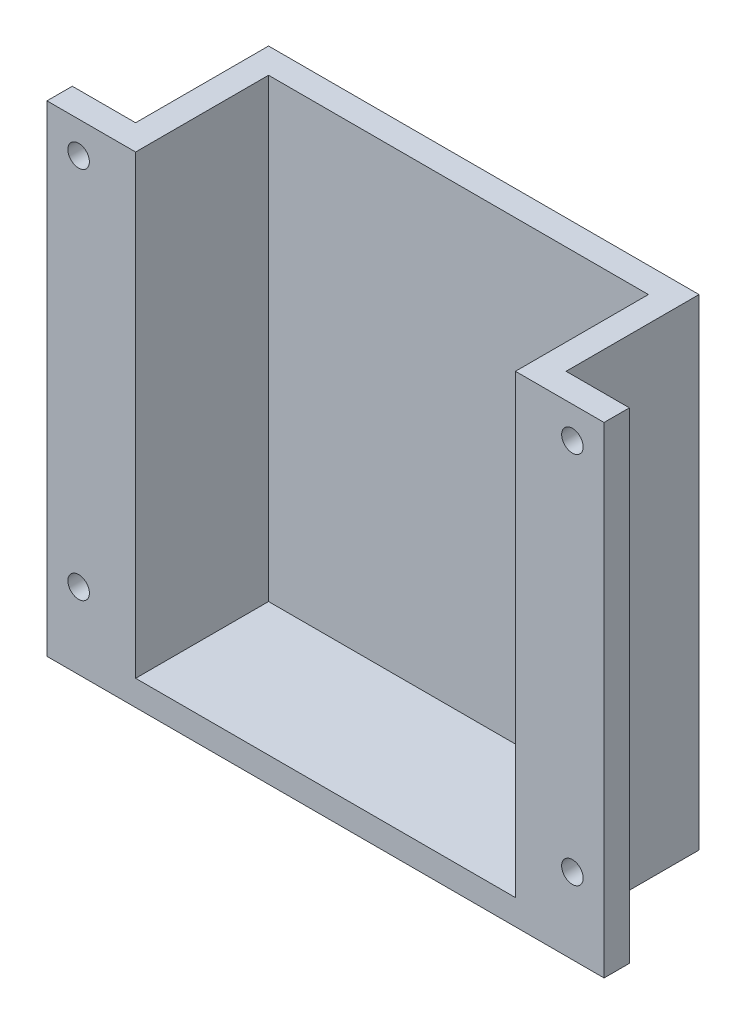
SolidWorks part; units mm, degrees
ref_plane "Front Plane" through (0, 0, 0) normal (0, 0, 1) x (1, 0, 0)
ref_plane "Top Plane" through (0, 0, 0) normal (0, 1, 0) x (1, 0, 0)
ref_plane "Right Plane" through (0, 0, 0) normal (1, 0, 0) x (0, 0, -1)
sketch "Sketch1" plane through (0, 0, 0) normal (0, 1, 0) x (1, 0, 0)
  line L0 (-48.1667, 0) -> (-38.1667, 0)
  line L1 (-38.1667, 0) -> (-38.1667, 21)
  line L2 (-38.1667, 21) -> (29.8333, 21)
  line L3 (29.8333, 21) -> (29.8333, 0)
  line L4 (29.8333, 0) -> (39.8333, 0)
  line L5 (-48.1667, 0) -> (-48.1667, -4)
  line L6 (-48.1667, -4) -> (-34.1667, -4)
  line L7 (-34.1667, -4) -> (-34.1667, 17)
  line L8 (-34.1667, 17) -> (25.8333, 17)
  line L9 (25.8333, 17) -> (25.8333, -4)
  line L10 (25.8333, -4) -> (39.8333, -4)
  line L11 (39.8333, 0) -> (39.8333, -4)
  dimension "D1" = 4
  dimension "D2" = 4
  dimension "D3" = 4
  dimension "D4" = 21
  dimension "D5" = 10
  dimension "D6" = 4
  dimension "D7" = 14
  dimension "D8" = 21
  dimension "D9" = 60
  dimension "D10" = 14
  dimension "D11" = 4
extrude "Boss-Extrude1" add sketch "Sketch1" along normal blind 76 contours L11 L10 L9 L8 L7 L6 L5 L0 L1 L2 L3 L4
sketch "Sketch2" plane through (0, 0, -17) normal (0, 0, 1) x (1, 0, 0)
  line L0 (-34.1667, 4) -> (25.8333, 4)
  line L1 (-34.1667, 76) -> (-34.1667, 0) construction
  line L2 (25.8333, 76) -> (25.8333, 0) construction
  line L3 (-34.1667, 0) -> (25.8333, 0) construction
  dimension "D1" = 4
extrude "Extrude-Thin1" add sketch "Sketch2" along normal blind 21 thin
sketch "Sketch4" plane through (0, 0, 0) normal (0, 0, -1) x (-1, 0, 0)
  line L0 (-29.8333, 76) -> (-39.8333, 76) construction
  line L1 (-39.8333, 76) -> (-39.8333, 0) construction
  line L2 (-29.8333, 0) -> (-39.8333, 0) construction
  line L3 (48.1667, 76) -> (38.1667, 76) construction
  line L4 (48.1667, 76) -> (48.1667, 0) construction
  line L5 (48.1667, 0) -> (38.1667, 0) construction
  circle A0 centre (-34.8333, 71) radius 1.7
  circle A1 centre (-34.8333, 12) radius 1.7
  circle A2 centre (43.1667, 71) radius 1.7
  circle A3 centre (43.1667, 12) radius 1.7
  dimension "D1" = 5
  dimension "D3" = 3.4
  dimension "D4" = 5
  dimension "D6" = 3.4
  dimension "D7" = 5
  dimension "D9" = 5
  dimension "D2" = 5
  dimension "D5" = 12
  dimension "D8" = 5
  dimension "D10" = 12
extrude "Cut-Extrude1" cut sketch "Sketch4" against normal blind 21
